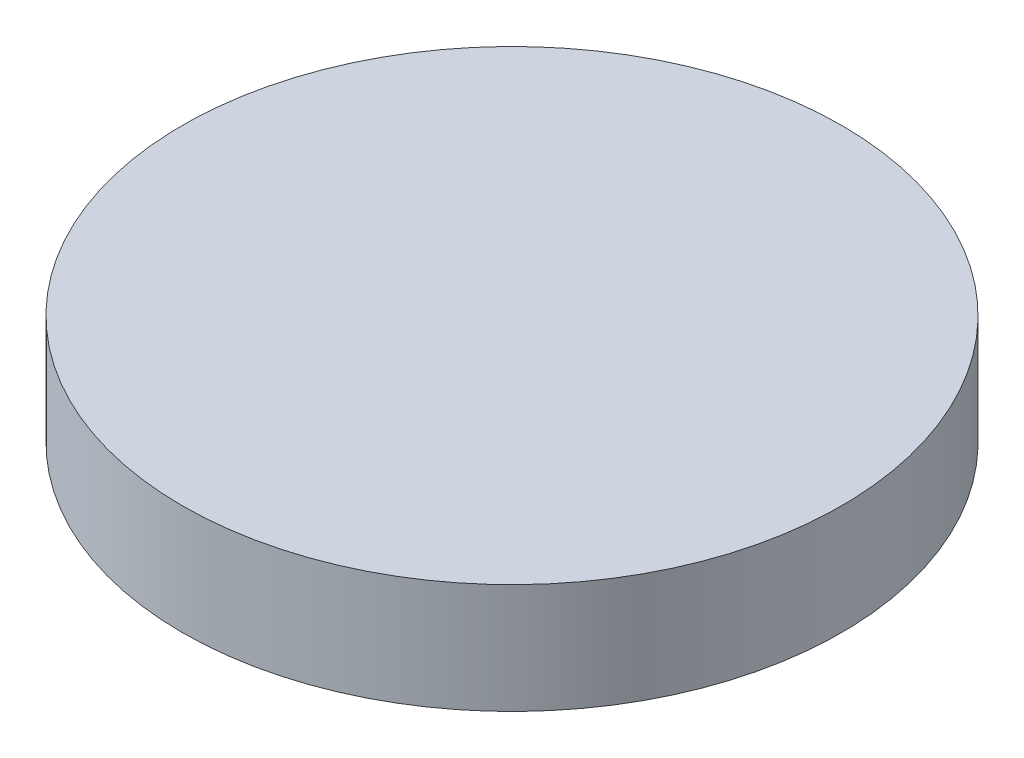
SolidWorks part; units mm, degrees
ref_plane "Front Plane" through (0, 0, 0) normal (0, 0, 1) x (1, 0, 0)
ref_plane "Top Plane" through (0, 0, 0) normal (0, 1, 0) x (1, 0, 0)
ref_plane "Right Plane" through (0, 0, 0) normal (1, 0, 0) x (0, 0, -1)
sketch "Sketch1" plane through (0, 0, 0) normal (0, 1, 0) x (1, 0, 0)
  circle A0 centre (0, 0) radius 4.7625
  dimension "D1" = 9.525
extrude "Boss-Extrude1" add sketch "Sketch1" along normal blind 1.5875
